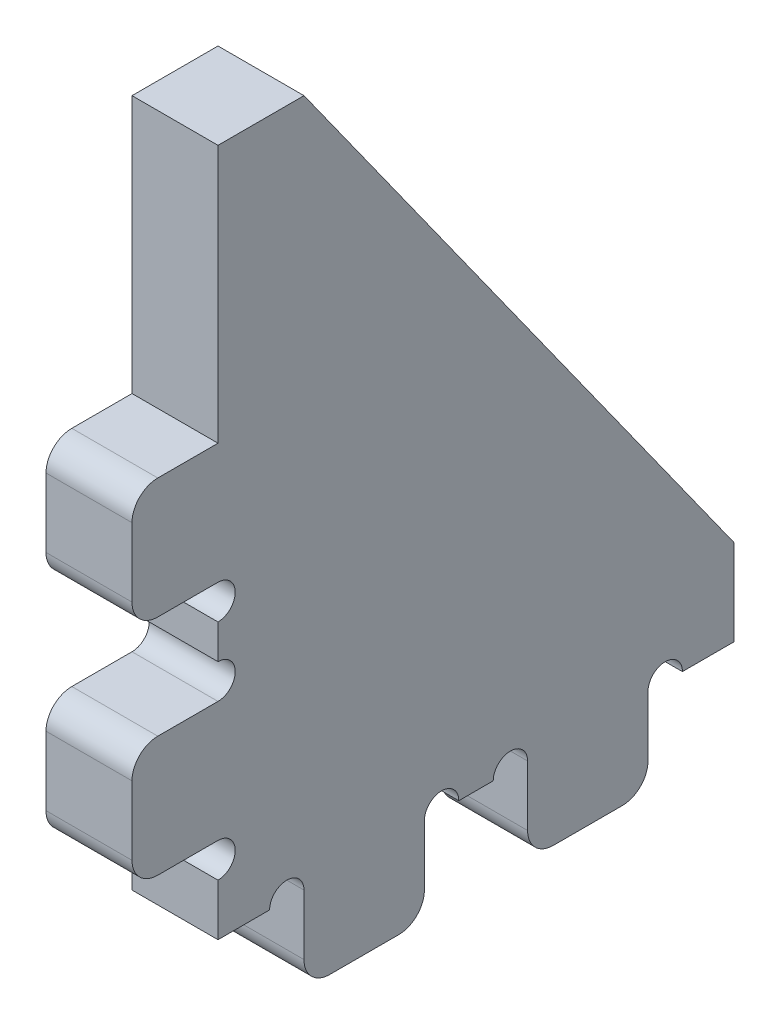
SolidWorks part; units mm, degrees
ref_plane "정면" through (0, 0, 0) normal (0, 0, 1) x (1, 0, 0)
ref_plane "윗면" through (0, 0, 0) normal (0, 1, 0) x (1, 0, 0)
ref_plane "우측면" through (0, 0, 0) normal (1, 0, 0) x (0, 0, -1)
sketch "스케치1" plane through (0, 0, 0) normal (1, 0, 0) x (0, 0, -1)
  line L0 (0, 0) -> (0, 40)
  line L1 (0, 40) -> (5, 40)
  line L2 (5, 40) -> (30, 5)
  line L3 (30, 5) -> (30, 0)
  line L4 (30, 0) -> (0, 0)
  dimension "D1" = 30
  dimension "D2" = 40
  dimension "D3" = 5
  dimension "D4" = 5
extrude "보스-돌출1" add sketch "스케치1" along normal blind 5
sketch "스케치2" plane through (5, 0, 0) normal (1, 0, 0) x (0, 0, -1)
  line L0 (0, 0) -> (30, 0) construction
  line L1 (5, 0) -> (12, 0)
  line L2 (5, 0) -> (5, -5)
  line L3 (5, -5) -> (12, -5)
  line L4 (12, 0) -> (12, -5)
  line L5 (18, -5) -> (12, -5) construction
  line L6 (18, 0) -> (25, 0)
  line L7 (18, 0) -> (18, -5)
  line L8 (18, -5) -> (25, -5)
  line L9 (25, 0) -> (25, -5)
  line L10 (0, 40) -> (0, 0) construction
  line L11 (30, 0) -> (30, 5) construction
  line L12 (0, 0) -> (15.5514, 15.5514) construction
  line L13 (-5, 18) -> (-5, 12) construction
  line L14 (0, 25) -> (-5, 25)
  line L15 (-5, 18) -> (-5, 25)
  line L16 (0, 18) -> (-5, 18)
  line L17 (0, 18) -> (0, 25)
  line L18 (0, 12) -> (-5, 12)
  line L19 (-5, 5) -> (-5, 12)
  line L20 (0, 5) -> (-5, 5)
  line L21 (0, 5) -> (0, 12)
  dimension "D1" = 5
  dimension "D2" = 7
  dimension "D3" = 7
  dimension "D4" = 5
  dimension "D5" = 5
  dimension "D6" = 45
extrude "보스-돌출2" add sketch "스케치2" against normal blind 5
sketch "스케치3" plane through (5, 0, 0) normal (1, 0, 0) x (0, 0, -1)
  line L0 (0, 0) -> (5, 0) construction
  line L1 (12, 0) -> (18, 0) construction
  line L2 (25, 0) -> (30, 0) construction
  line L3 (0, 5) -> (0, 0) construction
  line L4 (0, 18) -> (0, 12) construction
  circle A0 centre (4, 0) radius 1
  circle A1 centre (13, 0) radius 1
  circle A2 centre (17, 0) radius 1
  circle A3 centre (26, 0) radius 1
  circle A4 centre (0, 4) radius 1
  circle A5 centre (0, 13) radius 1
  circle A6 centre (0, 17) radius 1
  dimension "D1" = 2
extrude "컷-돌출1" cut sketch "스케치3" against normal blind 5
fillet "필렛1" radius 1.5 8 edges at (2.5, -5, -25) (2.5, -5, -12) (2.5, -5, -18) (2.5, 25, 5) (2.5, 18, 5) (2.5, -5, -5) (2.5, 5, 5) (2.5, 12, 5)
